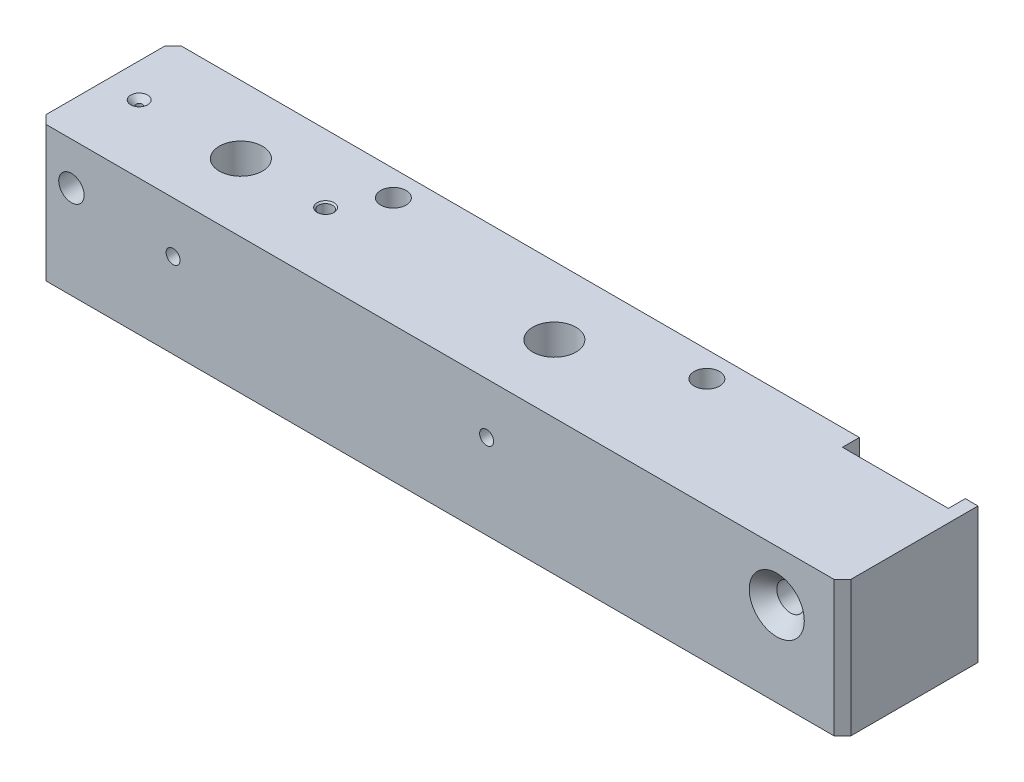
SolidWorks part; units mm, degrees
ref_plane "Front Plane" through (0, 0, 0) normal (0, 0, 1) x (1, 0, 0)
ref_plane "Top Plane" through (0, 0, 0) normal (0, 1, 0) x (1, 0, 0)
ref_plane "Right Plane" through (0, 0, 0) normal (1, 0, 0) x (0, 0, -1)
sketch "Sketch1" plane through (0, 0, 0) normal (0, 0, 1) x (1, 0, 0)
  line L1 (95, -16) -> (-95, -16)
  line L2 (95, -16) -> (95, 16)
  line L3 (95, 16) -> (-95, 16)
  line L4 (-95, -16) -> (-95, 16)
  line L5 (95, -16) -> (-95, 16) construction
  line L6 (95, 16) -> (-95, -16) construction
  point P0 (0, 0)
  dimension "D1" = 190
  dimension "D2" = 32
extrude "Boss-Extrude1" add sketch "Sketch1" along normal mid plane 32
sketch "Sketch2" plane through (0, 16, 0) normal (0, 1, 0) x (1, 0, 0)
  line L0 (95, 16) -> (-95, 16) construction
  line L1 (92, 16) -> (67, 16)
  line L2 (92, 16) -> (92, 12)
  line L3 (92, 12) -> (67, 12)
  line L4 (67, 16) -> (67, 12)
  line L5 (95, -16) -> (95, 16) construction
  dimension "D1" = 4
  dimension "D2" = 25
  dimension "D3" = 3
extrude "Cut-Extrude1" cut sketch "Sketch2" against normal through all
sketch "Sketch3" plane through (0, 16, 0) normal (0, 1, 0) x (1, 0, 0)
  line L0 (-95, 0) -> (95, 0) construction
  line L1 (-95, -16) -> (-95, 16) construction
  line L2 (95, -16) -> (95, 16) construction
  line L3 (-63, 16) -> (-63, -16) construction
  line L4 (67, 16) -> (-95, 16) construction
  line L5 (95, -16) -> (-95, -16) construction
  line L6 (11, 16) -> (11, -16) construction
  line L7 (67, 16) -> (67, 12) construction
  dimension "D1" = 56
  dimension "D2" = 74
hole_wizard "M12 Tapped Hole1" positions "Sketch5" profile "Sketch6" tap size "M12" standard "ISO"
sketch "Sketch5" plane through (0, 16, 0) normal (0, 1, 0) x (1, 0, 0)
  line L0 (-63, 16) -> (-63, -16) construction
  line L1 (11, 16) -> (11, -16) construction
  point P0 (-63, 0)
  point P4 (11, 0)
sketch "Sketch6" plane through (-63, 16, 0) normal (1, 0, 0) x (0, 0, 1)
  line L0 (0, 0) -> (0, 27.0644)
  line L1 (0, 27.0644) -> (5.1, 24)
  line L2 (5.1, 24) -> (5.1, 0)
  line L5 (5.1, 0) -> (0, 0)
  line L10 (0, 27.0644) -> (-5.1, 24) construction
  line L11 (0, -6.35) -> (0, 107.95) construction
  dimension "Tap Drill Dia." = 10.2
  dimension "Tap Drill Depth" = 24
  dimension "Drill Angle" = 118
cosmetic thread "Hole Thread1" parameters "D1"=24, "D2"=12
cosmetic thread "Hole Thread2" parameters "D1"=24, "D2"=12
sketch "Sketch7" plane through (0, 0, 16) normal (0, 0, 1) x (1, 0, 0)
  line L0 (-63, -8) -> (-63, 16) construction
  line L1 (-57.9, -8) -> (-68.1, -8) construction
  line L2 (-95, 16) -> (95, 16) construction
  line L3 (11, -8) -> (11, 16) construction
  line L4 (16.1, -8) -> (5.9, -8) construction
  line L5 (-63, 4) -> (11, 4) construction
hole_wizard "M4 Tapped Hole1" positions "Sketch8" profile "Sketch9" tap size "M4" standard "ISO"
sketch "Sketch8" plane through (0, 0, 16) normal (0, 0, 1) x (1, 0, 0)
  point P0 (-63, 4)
  point P3 (11, 4)
sketch "Sketch9" plane through (-63, 4, 16) normal (1, 0, 0) x (0, -1, 0)
  line L0 (0, 0) -> (0, 12.4914)
  line L1 (0, 12.4914) -> (1.65, 11.5)
  line L2 (1.65, 11.5) -> (1.65, 0)
  line L5 (1.65, 0) -> (0, 0)
  line L10 (0, 12.4914) -> (-1.65, 11.5) construction
  line L11 (0, -6.35) -> (0, 107.95) construction
  dimension "Tap Drill Dia." = 3.3
  dimension "Tap Drill Depth" = 11.5
  dimension "Drill Angle" = 118
cosmetic thread "Hole Thread3" parameters "D1"=8, "D2"=4
cosmetic thread "Hole Thread4" parameters "D1"=8, "D2"=4
sketch "Sketch13" plane through (0, 0, 16) normal (0, 0, 1) x (1, 0, 0)
  line L0 (-63, 4) -> (-87, 4) construction
  line L1 (-87, 4) -> (-87, 16) construction
  line L2 (-95, 16) -> (95, 16) construction
  line L3 (-95, -16) -> (95, -16) construction
  circle A0 centre (-87, 6) radius 3
  dimension "D1" = 6
  dimension "D2" = 22
  dimension "D3" = 24
extrude "Cut-Extrude2" cut sketch "Sketch13" against normal through all
hole_wizard "CSK for M4 Countersunk Flat Head Screw1" positions "Sketch14" profile "Sketch15" countersink size "M4" standard "ISO"
sketch "Sketch14" plane through (0, 16, 0) normal (0, 1, 0) x (1, 0, 0)
  line L0 (-95, 0) -> (95, 0) construction
  point P0 (-87, 0)
  dimension "D1" = 24
sketch "Sketch15" plane through (-87, 16, 0) normal (1, 0, 0) x (0, 0, 1)
  line L0 (0, 0) -> (0, 10.4506)
  line L1 (0, 10.4506) -> (0.75, 10)
  line L2 (0.75, 10) -> (0.75, 1.25)
  line L3 (0.75, 1.25) -> (2, 0)
  line L5 (2, 0) -> (0, 0)
  line L6 (-0.75, 1.25) -> (-2, 0) construction
  line L10 (0, 10.4506) -> (-0.75, 10) construction
  line L11 (0, -6.35) -> (0, 107.95) construction
  dimension "Hole Dia." = 1.5
  dimension "Hole Depth" = 10
  dimension "Near C'Sink Dia." = 4
  dimension "Near C'Sink Angle" = 90
  dimension "Drill Angle" = 118
hole_wizard "M4 Tapped Hole3" positions "Sketch24" profile "Sketch25" tap size "M4" standard "ISO"
sketch "Sketch24" plane through (0, 16, 0) normal (0, 1, 0) x (1, 0, 0)
  line L0 (-95, 0) -> (95, 0) construction
  point P0 (-43, 0)
  dimension "D1" = 20
sketch "Sketch25" plane through (-43, 16, 0) normal (1, 0, 0) x (0, 0, 1)
  line L0 (0, 0) -> (0, 16.9914)
  line L1 (0, 16.9914) -> (1.65, 16)
  line L2 (1.65, 16) -> (1.65, 0.35)
  line L3 (1.65, 0.35) -> (2, 0)
  line L5 (2, 0) -> (0, 0)
  line L6 (-1.65, 0.35) -> (-2, 0) construction
  line L10 (0, 16.9914) -> (-1.65, 16) construction
  line L11 (0, -6.35) -> (0, 107.95) construction
  dimension "Tap Drill Dia." = 3.3
  dimension "Tap Drill Depth" = 16
  dimension "Near C'Sink Dia." = 4
  dimension "Near C'Sink Angle" = 90
  dimension "Drill Angle" = 118
cosmetic thread "Hole Thread6" parameters "D1"=8, "D2"=4
sketch "Sketch26" plane through (0, 16, 0) normal (0, 1, 0) x (1, 0, 0)
  line L0 (-95, -16) -> (-95, 16) construction
  line L1 (67, 16) -> (-95, 16) construction
  circle A0 centre (-37, 10) radius 3
  circle A1 centre (37, 10) radius 3
  dimension "D4" = 6
  dimension "D5" = 6
  dimension "D1" = 74
  dimension "D2" = 58
  dimension "D3" = 6
extrude "Cut-Extrude4" cut sketch "Sketch26" against normal blind 32
hole_wizard "CSK for M10 Countersunk Flat Head Screw3" positions "Sketch33" profile "Sketch34" countersink size "M10" standard "ISO" end condition through all
sketch "Sketch33" plane through (0, 0, 16) normal (0, 0, 1) x (1, 0, 0)
  line L0 (95, -16) -> (95, 16) construction
  line L1 (-95, -16) -> (95, -16) construction
  point P0 (79.5, 4)
  dimension "D1" = 15.5
  dimension "D2" = 20
sketch "Sketch34" plane through (79.5, 4, 16) normal (1, 0, 0) x (0, -1, 0)
  line L0 (0, 0) -> (0, 32)
  line L1 (0, 32) -> (3.25, 32)
  line L2 (3.25, 32) -> (3.25, 3.25)
  line L3 (3.25, 3.25) -> (6.5, 0)
  line L5 (6.5, 0) -> (0, 0)
  line L6 (-3.25, 3.25) -> (-6.5, 0) construction
  line L11 (0, -6.35) -> (0, 107.95) construction
  dimension "Thru Hole Dia." = 6.5
  dimension "Thru Hole Depth" = 32
  dimension "Near C'Sink Dia." = 13
  dimension "Near C'Sink Angle" = 90
chamfer "Chamfer3" distance 2 angle 45 3 edges at (-95, 0, -16) (-95, 0, 16) (95, 0, 16)
